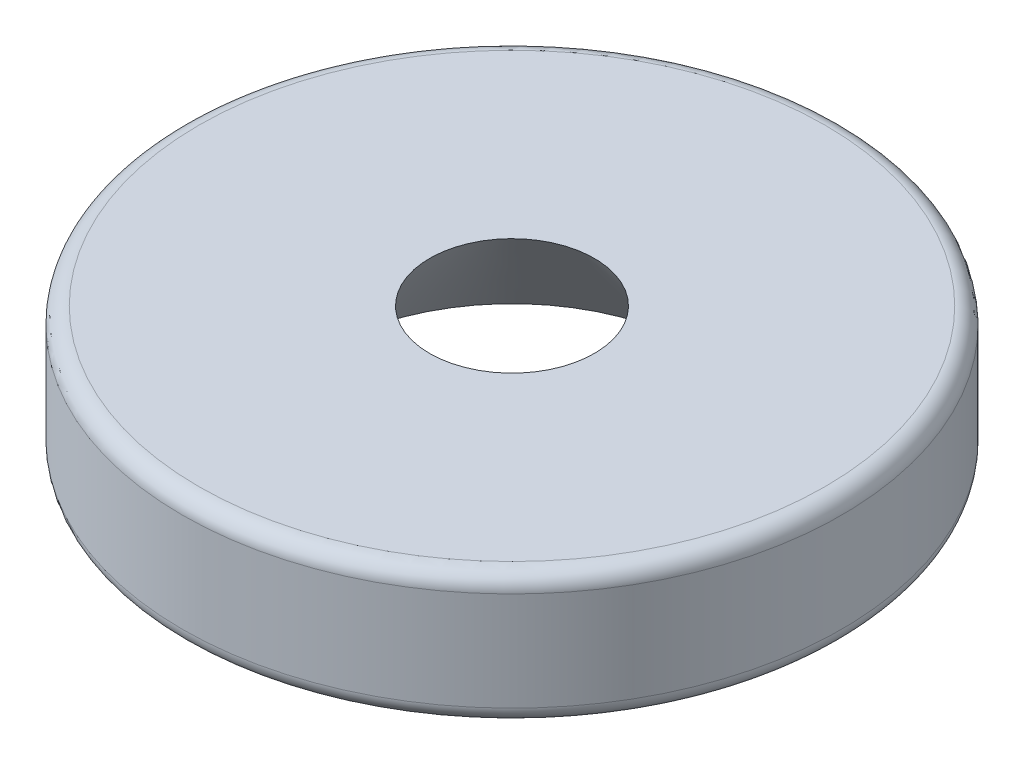
SolidWorks part; units mm, degrees
ref_plane "前视基准面" through (0, 0, 0) normal (0, 0, 1) x (1, 0, 0)
ref_plane "上视基准面" through (0, 0, 0) normal (0, 1, 0) x (1, 0, 0)
ref_plane "右视基准面" through (0, 0, 0) normal (1, 0, 0) x (0, 0, -1)
sketch "草图1" plane through (0, 0, 0) normal (0, 1, 0) x (1, 0, 0)
  circle A0 centre (0, 0) radius 10
  dimension "D1" = 20
extrude "凸台-拉伸1" add sketch "草图1" along normal blind 4
sketch "草图2" plane through (0, 4, 0) normal (0, 1, 0) x (1, 0, 0)
  circle A0 centre (0, 0) radius 2.5
  dimension "D1" = 5
extrude "切除-拉伸1" cut sketch "草图2" against normal blind 4 draft 39 draft outward yes
fillet "圆角2" radius 0.5 1 edges at (0, 0, 10)
fillet "圆角3" radius 0.5 1 edges at (0, 4, 10)
